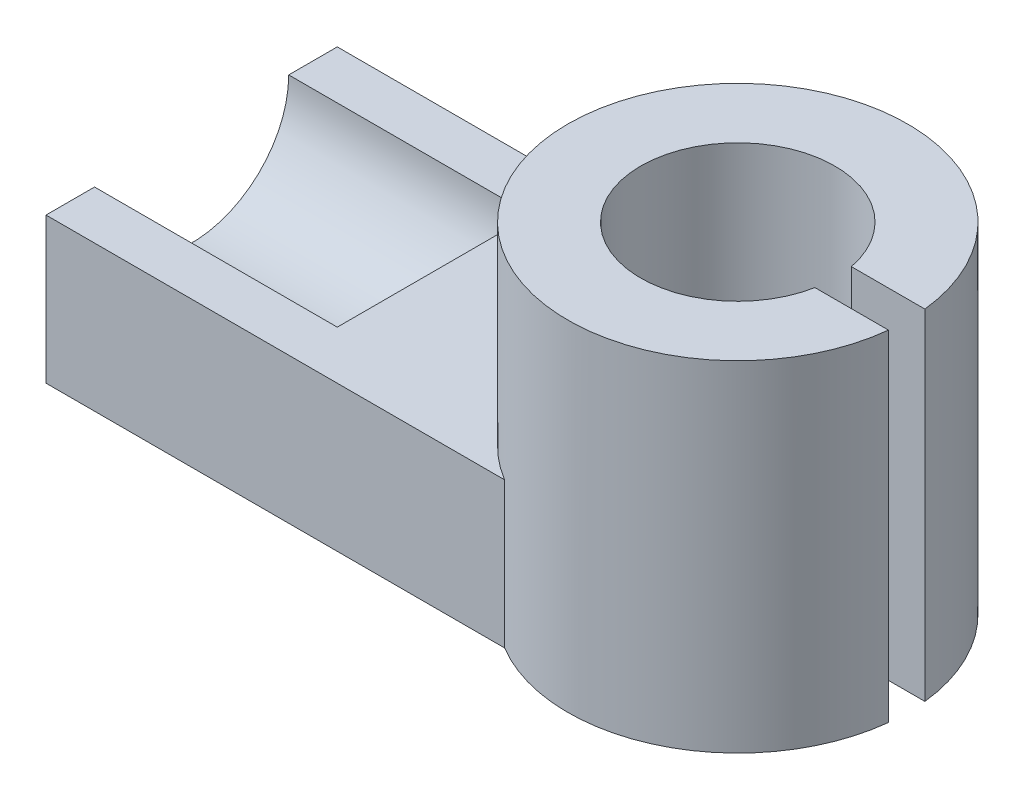
SolidWorks part; units mm, degrees
ref_plane "Front Plane" through (0, 0, 0) normal (0, 0, 1) x (1, 0, 0)
ref_plane "Top Plane" through (0, 0, 0) normal (0, 1, 0) x (1, 0, 0)
ref_plane "Right Plane" through (0, 0, 0) normal (1, 0, 0) x (0, 0, -1)
sketch "Sketch1" plane through (0, 0, 0) normal (0, 1, 0) x (1, 0, 0)
  line L1 (15.7162, -3) -> (27.8388, -3)
  line L3 (15.7162, 3) -> (27.8388, 3)
  arc A0 (15.7162, 3) -> (15.7162, -3) centre (0, 0) ccw
  circle A1 centre (0, 0) radius 28
  point P4 (16, 0)
  dimension "D1" = 56
  dimension "D2" = 32
extrude "Boss-Extrude1" add sketch "Sketch1" along normal blind 56 contours L3 A1 L1 A0
sketch "Sketch3" plane through (0, 0, 0) normal (0, -1, 0) x (1, 0, 0)
  line L0 (0, 0) -> (-113.597, 0) construction
  line L1 (-90, -24) -> (-14.4222, -24)
  line L2 (-90, -24) -> (-90, 24)
  line L3 (-90, 24) -> (-14.4222, 24)
  arc A0 (27.8388, 3) -> (27.8388, -3) centre (0, 0) ccw construction
  arc A1 (-14.4222, 24) -> (-14.4222, -24) centre (0, 0) ccw
  point P7 (0, 0)
  point P8 (0, 0)
  point P9 (-113.597, 0)
  dimension "D1" = 48
  dimension "D2" = 90
extrude "Boss-Extrude2" add sketch "Sketch3" against normal blind 24
sketch "Sketch5" plane through (-90, 0, 0) normal (-1, 0, 0) x (0, 0, 1)
  line L0 (24, 24) -> (-24, 24) construction
  circle A0 centre (0, 24) radius 16
  dimension "D1" = 32
extrude "Cut-Extrude1" cut sketch "Sketch5" against normal blind 40
